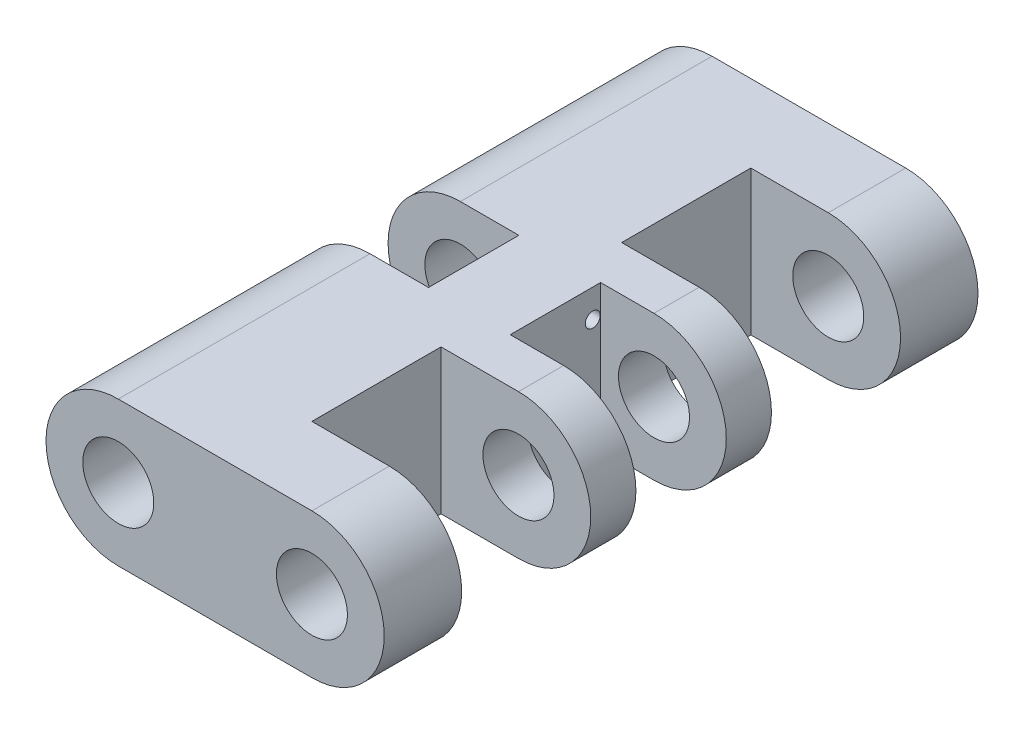
SolidWorks part; units mm, degrees
ref_plane "Front Plane" through (0, 0, 0) normal (0, 0, 1) x (1, 0, 0)
ref_plane "Top Plane" through (0, 0, 0) normal (0, 1, 0) x (1, 0, 0)
ref_plane "Right Plane" through (0, 0, 0) normal (1, 0, 0) x (0, 0, -1)
sketch "Sketch1" plane through (0, 0, 0) normal (0, 0, 1) x (1, 0, 0)
  line L0 (0, 0) -> (19.05, 0) construction
  line L1 (0, 7.112) -> (19.05, 7.112)
  line L2 (0, -7.112) -> (19.05, -7.112)
  circle A0 centre (0, 0) radius 3.4925
  circle A1 centre (19.05, 0) radius 3.4925
  arc A2 (0, 7.112) -> (0, -7.112) centre (0, 0) ccw
  arc A3 (19.05, -7.112) -> (19.05, 7.112) centre (19.05, 0) ccw
  point P5 (9.525, 0)
  dimension "D1" = 6.985
  dimension "D2" = 19.05
  dimension "D3" = 7.112
extrude "Boss-Extrude1" add sketch "Sketch1" along normal blind 58.42
sketch "Sketch2" plane through (0, 7.112, 0) normal (0, 1, 0) x (1, 0, 0)
  line L0 (19.05, 0) -> (0, 0) construction
  line L1 (11.43, -20.32) -> (33.3144, -20.32)
  line L2 (11.43, -20.32) -> (11.43, -7.62)
  line L3 (11.43, -7.62) -> (33.3144, -7.62)
  line L4 (33.3144, -20.32) -> (33.3144, -7.62)
  line L5 (11.43, -20.32) -> (33.3144, -7.62) construction
  line L6 (11.43, -7.62) -> (33.3144, -20.32) construction
  line L7 (26.162, -58.42) -> (26.162, 0) construction
  line L12 (37.955, -50.8) -> (11.43, -50.8)
  line L13 (37.955, -50.8) -> (37.955, -38.1)
  line L14 (37.955, -38.1) -> (11.43, -38.1)
  line L15 (11.43, -50.8) -> (11.43, -38.1)
  line L16 (37.955, -50.8) -> (11.43, -38.1) construction
  line L17 (37.955, -38.1) -> (11.43, -50.8) construction
  line L18 (0, -58.42) -> (0, 0) construction
  line L19 (26.4973, -33.655) -> (13.7973, -33.655)
  line L20 (26.4973, -33.655) -> (26.4973, -24.765)
  line L21 (26.4973, -24.765) -> (13.7973, -24.765)
  line L22 (13.7973, -33.655) -> (13.7973, -24.765)
  line L23 (26.4973, -33.655) -> (13.7973, -24.765) construction
  line L24 (26.4973, -24.765) -> (13.7973, -33.655) construction
  point P0 (22.3722, -13.97)
  point P7 (24.6925, -44.45)
  point P21 (17.7036, -26.2341)
  point P22 (0, 0)
  point P23 (26.162, -29.21)
  point P24 (0, -29.21)
  point P25 (20.1473, -29.21)
  dimension "D1" = 7.62
  dimension "D2" = 12.7
  dimension "D3" = 12.7
  dimension "D4" = 7.62
  dimension "D5" = 14.732
  dimension "D6" = 8.89
  dimension "D7" = 12.7
extrude "Cut-Extrude1" cut sketch "Sketch2" against normal up to surface (14.224 mm away) up to face at (9.525, -7.112, 29.21)
sketch "Sketch4" plane through (0, 7.112, 0) normal (0, 1, 0) x (1, 0, 0)
  line L0 (13.7973, -24.765) -> (13.7973, -33.655) construction
  line L1 (5.7539, -24.765) -> (-10.2434, -24.765)
  line L2 (5.7539, -24.765) -> (5.7539, -33.655)
  line L3 (5.7539, -33.655) -> (-10.2434, -33.655)
  line L4 (-10.2434, -24.765) -> (-10.2434, -33.655)
  line L5 (5.7539, -24.765) -> (-10.2434, -33.655) construction
  line L6 (5.7539, -33.655) -> (-10.2434, -24.765) construction
  point P0 (-2.2447, -29.21)
  point P5 (0, 0)
  point P8 (13.7973, -29.21)
  dimension "D1" = 8.89
extrude "Cut-Extrude2" cut sketch "Sketch4" against normal up to surface (14.224 mm away) up to face at (14.1072, -7.112, 29.21)
sketch "Sketch5" plane through (5.7539, 0, 0) normal (-1, 0, 0) x (0, 0, 1)
  circle A0 centre (25.5373, 4.3399) radius 0.7366
  circle A2 centre (32.9033, 4.3399) radius 1.016
  point P2 (32.6092, 4.3399)
  point P3 (25.5373, 4.3399)
  point P8 (25.1201, 4.3)
  point P9 (23.6214, 11.4421)
  dimension "D1" = 1.4732
  dimension "D2" = 2.032
  dimension "D3" = 7.366
extrude "Cut-Extrude3" cut sketch "Sketch5" against normal blind 12.7
